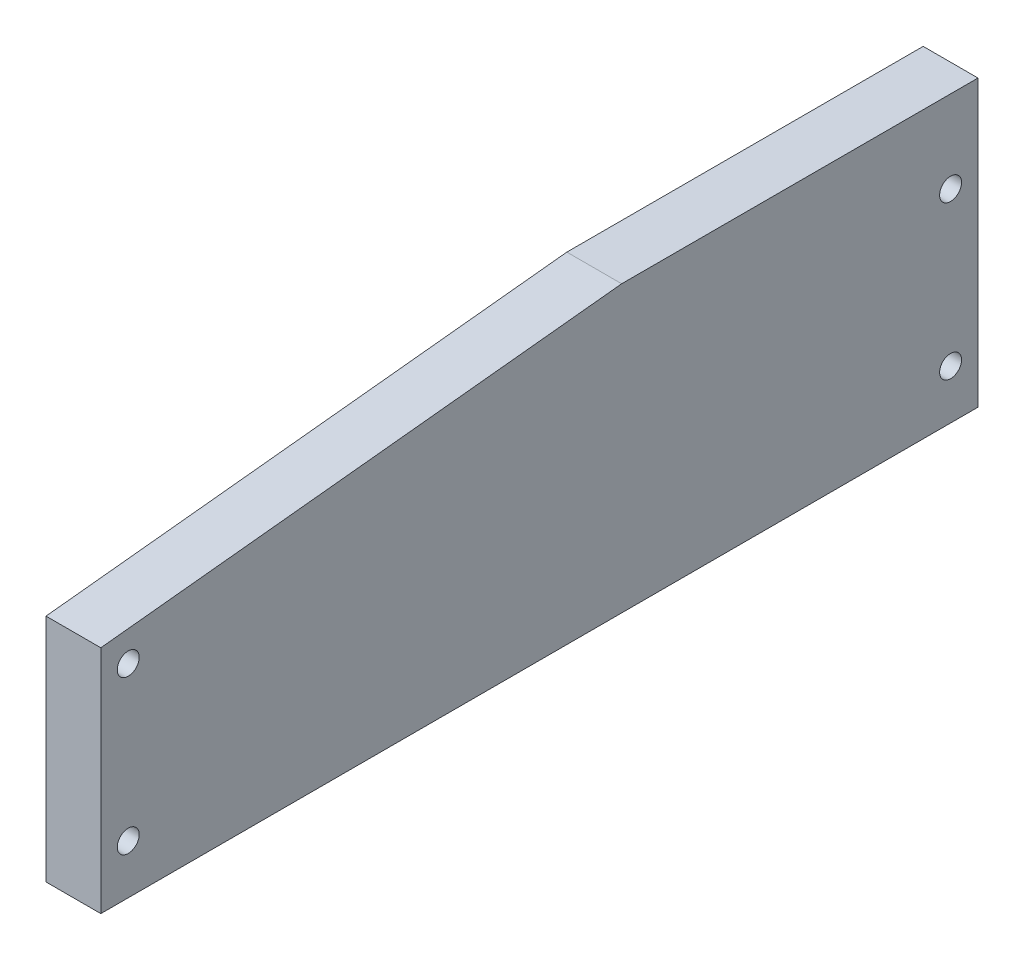
SolidWorks part; units mm, degrees
material "Mahogany"
ref_plane "Front Plane" through (0, 0, 0) normal (0, 0, 1) x (1, 0, 0)
ref_plane "Top Plane" through (0, 0, 0) normal (0, 1, 0) x (1, 0, 0)
ref_plane "Right Plane" through (0, 0, 0) normal (1, 0, 0) x (0, 0, -1)
sketch "Sketch3" plane through (0, 0, 0) normal (1, 0, 0) x (0, 0, -1)
  line L0 (18.5944, 46.9577) -> (18.5944, -5.0423)
  line L1 (18.5944, -5.0423) -> (-141.4056, -5.0423)
  line L2 (-141.4056, -5.0423) -> (-141.4056, 36.9577)
  line L3 (-141.4056, 36.9577) -> (-46.4056, 46.9577)
  line L4 (-46.4056, 46.9577) -> (18.5944, 46.9577)
  dimension "D1" = 42
  dimension "D2" = 65
  dimension "D3" = 52
  dimension "D4" = 160
extrude "Boss-Extrude1" add sketch "Sketch3" along normal blind 10 contours L0 L1 L2 L3 L4
sketch "Sketch4" plane through (10, 0, 0) normal (1, 0, 0) x (0, 0, -1)
  line L0 (-46.4056, 46.9577) -> (18.5944, 46.9577) construction
  line L1 (-141.4056, -5.0423) -> (-141.4056, 36.9577) construction
  line L2 (18.5944, -5.0423) -> (-141.4056, -5.0423) construction
  line L3 (18.5944, 46.9577) -> (18.5944, -5.0423) construction
  circle A0 centre (-136.4056, 31.9577) radius 2
  circle A1 centre (-136.4056, 3.9577) radius 2
  circle A2 centre (13.5944, 3.9577) radius 2
  circle A3 centre (13.5944, 31.9577) radius 2
  dimension "D1" = 4
  dimension "D4" = 4
  dimension "D6" = 4
  dimension "D8" = 4
  dimension "D2" = 15
  dimension "D3" = 5
  dimension "D5" = 9
  dimension "D7" = 5
extrude "Cut-Extrude1" cut sketch "Sketch4" against normal blind 5
